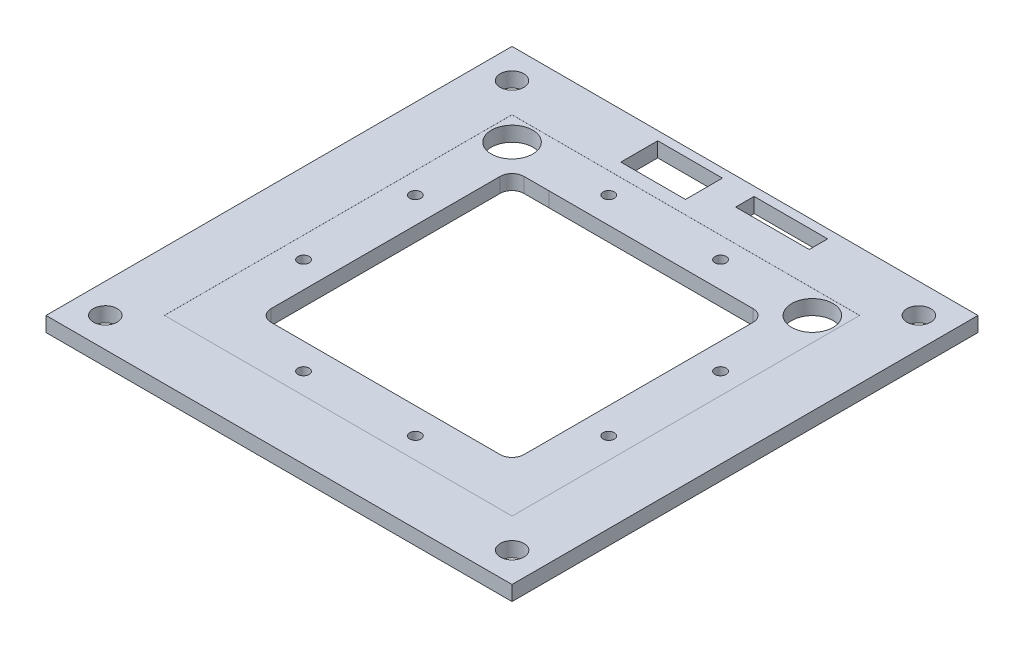
SolidWorks part; units mm, degrees
ref_plane "Front Plane" through (0, 0, 0) normal (0, 0, 1) x (1, 0, 0)
ref_plane "Top Plane" through (0, 0, 0) normal (0, 1, 0) x (1, 0, 0)
ref_plane "Right Plane" through (0, 0, 0) normal (1, 0, 0) x (0, 0, -1)
sketch "Sketch1" plane through (0, 0, 0) normal (0, 1, 0) x (1, 0, 0)
  line L0 (-100.0125, 99.9889) -> (-87.3125, 99.9889) construction
  line L1 (-100.0125, -100.0361) -> (100.0125, -100.0361)
  line L2 (-100.0125, -100.0361) -> (-100.0125, 99.9889)
  line L3 (-100.0125, 99.9889) -> (100.0125, 99.9889)
  line L4 (100.0125, -100.0361) -> (100.0125, 99.9889)
  line L5 (-100.0125, -100.0361) -> (100.0125, 99.9889) construction
  line L6 (-100.0125, 99.9889) -> (100.0125, -100.0361) construction
  line L7 (-74.6125, -74.6125) -> (74.6125, -74.6125) construction
  line L8 (-74.6125, -74.6125) -> (-74.6125, 74.6125) construction
  line L9 (-74.6125, 74.6125) -> (74.6125, 74.6125) construction
  line L10 (74.6125, -74.6125) -> (74.6125, 74.6125) construction
  line L11 (-74.6125, -74.6125) -> (74.6125, 74.6125) construction
  line L12 (-74.6125, 74.6125) -> (74.6125, -74.6125) construction
  line L13 (-87.3125, 99.9889) -> (-87.3125, -100.0361) construction
  line L14 (0, -55) -> (0, 55) construction
  line L15 (-55, 0) -> (55, 0) construction
  line L16 (-100.0125, 96.1789) -> (100.0125, 96.1789) construction
  line L18 (-33.6459, 96.1789) -> (-5.887, 96.1789)
  line L19 (-33.6459, 96.1789) -> (-33.6459, 80.3284)
  line L20 (-33.6459, 80.3284) -> (-5.887, 80.3284)
  line L21 (-5.887, 96.1789) -> (-5.887, 80.3284)
  line L22 (7.7239, 96.1789) -> (39.2871, 96.1789)
  line L23 (7.7239, 96.1789) -> (7.7239, 88.2654)
  line L24 (7.7239, 88.2654) -> (39.2871, 88.2654)
  line L25 (39.2871, 96.1789) -> (39.2871, 88.2654)
  line L33 (54.27, -38.5) -> (54.27, 38.5)
  line L47 (54.27, -38.5) -> (54.27, -42.77)
  line L54 (42.77, -54.27) -> (38.5, -54.27)
  line L56 (38.5, -54.27) -> (-38.5, -54.27)
  line L57 (-42.77, -54.27) -> (-38.5, -54.27)
  line L64 (38.5, 54.27) -> (54.2936, 54.27)
  line L67 (-54.27, -38.5) -> (-54.27, 38.5)
  line L69 (54.2936, 54.27) -> (54.27, 38.5)
  line L70 (49, -49) -> (-49, 49) construction
  line L71 (49, 49) -> (-49, -49) construction
  line L72 (42.77, -54.27) -> (54.2464, -54.27)
  line L73 (54.2464, -54.27) -> (54.27, -42.77)
  line L74 (-54.27, 38.5) -> (-54.27, 54.2464)
  line L75 (-54.27, 54.2464) -> (-38.5, 54.27)
  line L76 (0, 53) -> (0, -53) construction
  line L78 (-54.27, -38.5) -> (-54.27, -54.2936)
  line L83 (-54.27, -54.2936) -> (-42.77, -54.27)
  line L86 (-38.5, 54.27) -> (38.5, 54.27)
  circle A0 centre (-87.3125, 87.2889) radius 5.08
  circle A1 centre (87.3125, 87.2889) radius 5.08
  circle A2 centre (-87.3125, -87.2889) radius 5.08
  circle A3 centre (87.3125, -87.2889) radius 5.08
  point P6 (0, 54.27)
  point P11 (-87.3125, 87.2889)
  point P60 (0, -54.27)
  dimension "D5" = 10.16
  dimension "D7" = 85.54
  dimension "D1" = 200.025
  dimension "D2" = 200.025
  dimension "D3" = 149.225
  dimension "D4" = 12.7
  dimension "D6" = 3.81
extrude "Boss-Extrude1" add sketch "Sketch1" along normal blind 6.35
fillet "Fillet1" radius 5.08 4 edges at (54.2464, 3.175, 54.27) (-54.27, 3.175, 54.2936) (54.2936, 3.175, -54.27) (-54.27, 3.175, -54.2464)
sketch "Sketch3" plane through (0, 0, 0) normal (0, -1, 0) x (1, 0, 0)
  circle A2 centre (-24, 65.5) radius 2.4
  circle A3 centre (24, 65.5) radius 2.4
  circle A10 centre (-24, 65.5) radius 2.4 construction
  circle A11 centre (24, 65.5) radius 2.4 construction
  circle A12 centre (65.5, 24) radius 2.4
  circle A13 centre (65.5, -24) radius 2.4
  circle A14 centre (24, -65.5) radius 2.4
  circle A15 centre (-24, -65.5) radius 2.4
  circle A16 centre (-65.5, -24) radius 2.4
  circle A17 centre (-65.5, 24) radius 2.4
  dimension "D1" = 4
extrude "Cut-Extrude1" cut sketch "Sketch3" against normal through all
sketch "Sketch4" plane through (0, 6.35, 0) normal (0, 1, 0) x (1, 0, 0)
  line L0 (-100.0125, -100.0361) -> (100.0125, -100.0361) construction
  line L1 (-100.0125, 99.9889) -> (100.0125, 99.9889)
  line L2 (-100.0125, 99.9889) -> (-100.0125, -100.0361)
  line L3 (-100.0125, -100.0361) -> (100.0125, -100.0361)
  line L4 (100.0125, 99.9889) -> (100.0125, -100.0361)
  line L5 (100.0125, -100.0361) -> (100.0125, 99.9889) construction
  line L7 (-74.6125, -74.5889) -> (74.6125, -74.5889)
  line L8 (-74.6125, -74.5889) -> (-74.6125, 74.5889)
  line L9 (-74.6125, 74.5889) -> (74.6125, 74.5889)
  line L10 (74.6125, -74.5889) -> (74.6125, 74.5889)
  line L11 (-74.6125, -74.5889) -> (74.6125, 74.5889) construction
  line L12 (-74.6125, 74.5889) -> (74.6125, -74.5889) construction
  line L13 (-33.6459, 96.1789) -> (-5.887, 96.1789)
  line L14 (-33.6459, 96.1789) -> (-33.6459, 80.3284)
  line L15 (-33.6459, 80.3284) -> (-5.887, 80.3284)
  line L16 (-5.887, 96.1789) -> (-5.887, 80.3284)
  line L17 (7.7239, 96.1789) -> (39.2871, 96.1789)
  line L18 (7.7239, 96.1789) -> (7.7239, 88.2654)
  line L19 (7.7239, 88.2654) -> (39.2871, 88.2654)
  line L20 (39.2871, 96.1789) -> (39.2871, 88.2654)
  circle A0 centre (-87.3125, 87.2889) radius 5.08
  circle A1 centre (87.3125, 87.2889) radius 5.08
  circle A2 centre (87.3125, -87.2889) radius 5.08
  circle A3 centre (-87.3125, -87.2889) radius 5.08
  point P21 (0, 0)
  dimension "D1" = 25.4
  dimension "D2" = 25.4
extrude "Boss-Extrude2" add sketch "Sketch4" along normal blind 0.0254
sketch "Sketch5" plane through (0, 6.35, 0) normal (0, 1, 0) x (1, 0, 0)
  line L0 (74.6125, 74.5889) -> (-74.6125, 74.5889) construction
  line L1 (-74.6125, 74.5889) -> (-74.6125, -74.5889) construction
  line L2 (0, -3.4925) -> (0, 3.4925) construction
  circle A0 centre (-64.4525, 64.455) radius 8.89
  circle A1 centre (64.4525, 64.455) radius 8.89
  dimension "D3" = 17.78
  dimension "D1" = 10.1338
  dimension "D2" = 10.16
extrude "Cut-Extrude2" cut sketch "Sketch5" against normal through all
